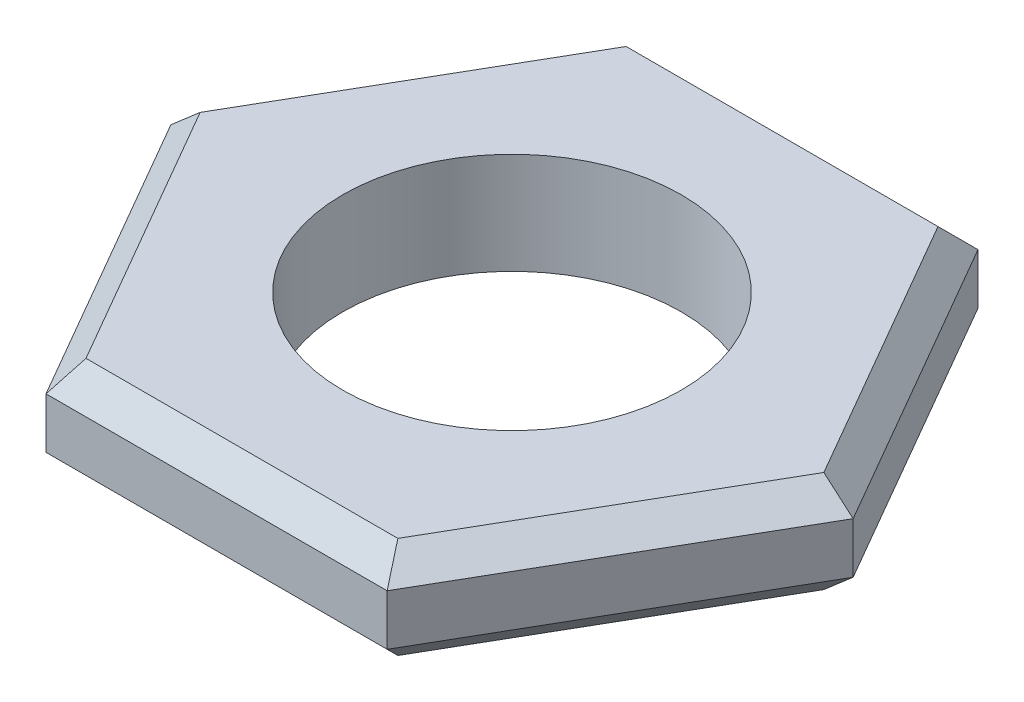
SolidWorks part; units mm, degrees
material "ABS"
ref_plane "Front Plane" through (0, 0, 0) normal (0, 0, 1) x (1, 0, 0)
ref_plane "Top Plane" through (0, 0, 0) normal (0, 1, 0) x (1, 0, 0)
ref_plane "Right Plane" through (0, 0, 0) normal (1, 0, 0) x (0, 0, -1)
sketch "Sketch1" plane through (0, 0, 0) normal (0, 1, 0) x (1, 0, 0)
  line L1 (6.8337, 11.8364) -> (-6.8337, 11.8364)
  line L2 (-6.8337, 11.8364) -> (-13.6675, 0)
  line L3 (-13.6675, 0) -> (-6.8337, -11.8364)
  line L4 (-6.8337, -11.8364) -> (6.8337, -11.8364)
  line L5 (6.8337, -11.8364) -> (13.6675, 0)
  line L6 (13.6675, 0) -> (6.8337, 11.8364)
  circle A0 centre (0, 0) radius 11.8364 construction
  circle A1 centre (0, 0) radius 6.7818
  dimension "D2" = 13.5636
  dimension "D1" = 23.6728
extrude "Boss-Extrude1" add sketch "Sketch1" along normal mid plane 4.064
chamfer "Chamfer1" distance 1.016 angle 45 12 edges at (-10.2506, -2.032, -5.9182) (0, -2.032, -11.8364) (10.2506, -2.032, -5.9182) (-10.2506, -2.032, 5.9182) (0, -2.032, 11.8364) (10.2506, -2.032, 5.9182) (10.2506, 2.032, 5.9182) (10.2506, 2.032, -5.9182) (0, 2.032, -11.8364) (-10.2506, 2.032, -5.9182) (-10.2506, 2.032, 5.9182) (0, 2.032, 11.8364)
